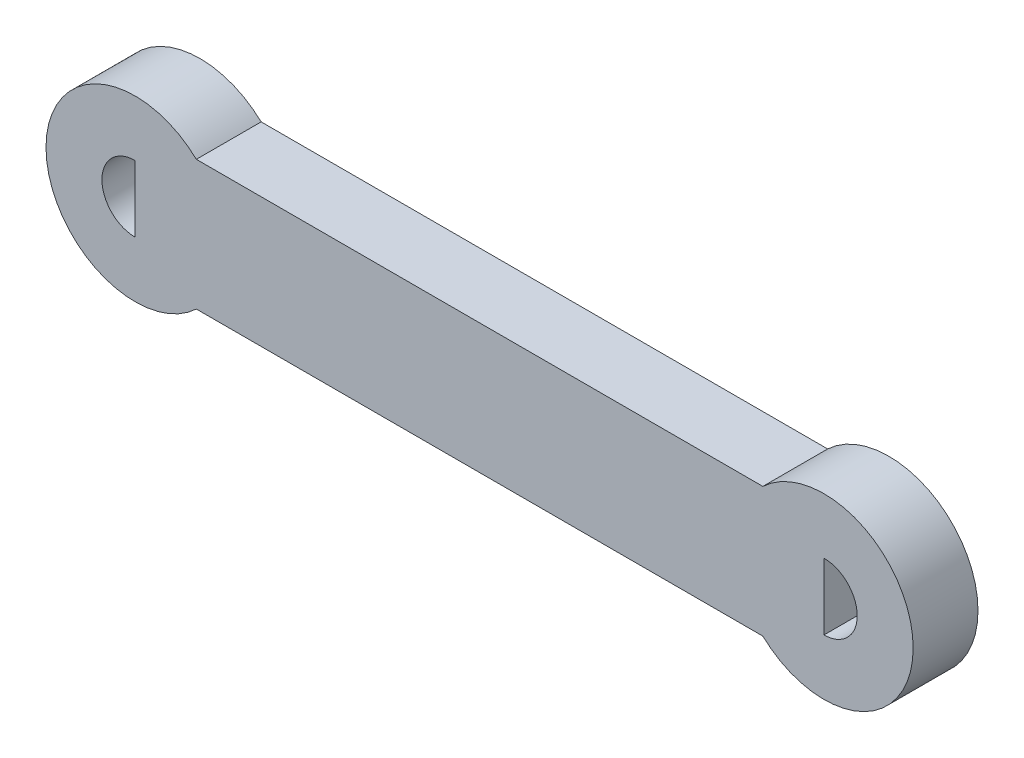
SolidWorks part; units mm, degrees
ref_plane "前视基准面" through (0, 0, 0) normal (0, 0, 1) x (1, 0, 0)
ref_plane "上视基准面" through (0, 0, 0) normal (0, 1, 0) x (1, 0, 0)
ref_plane "右视基准面" through (0, 0, 0) normal (1, 0, 0) x (0, 0, -1)
other "Configuration Table"
sketch "草图1" plane through (0, 0, 0) normal (0, 0, 1) x (1, 0, 0)
  line L0 (0, -8) -> (85, -8)
  line L1 (85, -8) -> (85, 8)
  line L2 (85, 8) -> (0, 8)
  line L3 (0, 8) -> (0, -8)
extrude "凸台-拉伸1" add sketch "草图1" along normal blind 8
sketch "草图2" plane through (0, 0, 0) normal (0, 0, 1) x (1, 0, 0)
  circle A0 centre (0, 0) radius 11
  circle A1 centre (0, 0) radius 4.1
extrude "凸台-拉伸2" add sketch "草图2" along normal blind 8
sketch "草图3" plane through (0, 0, 0) normal (0, 0, 1) x (1, 0, 0)
  line L0 (85, -8) -> (85, 8) construction
  circle A0 centre (85, 0) radius 11
  circle A1 centre (85, 0) radius 4.1
extrude "凸台-拉伸3" add sketch "草图3" along normal blind 8
